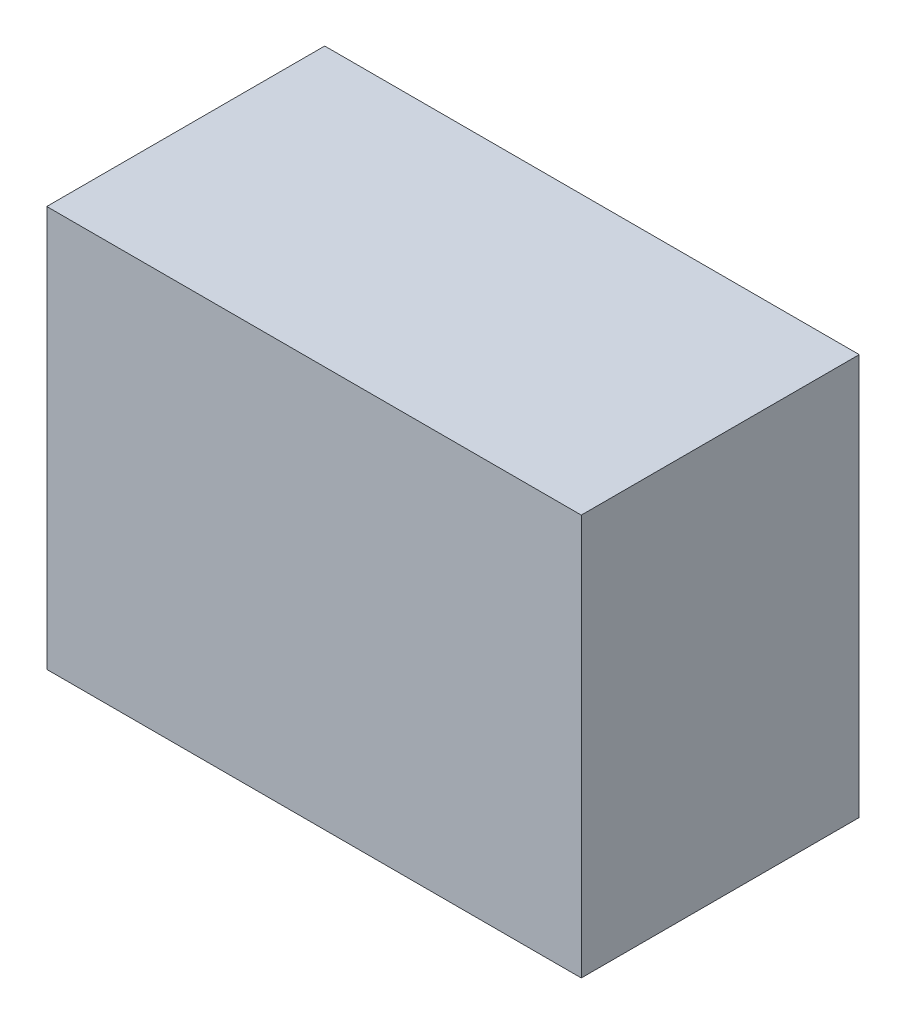
SolidWorks part; units mm, degrees
ref_plane "Front Plane" through (0, 0, 0) normal (0, 0, 1) x (1, 0, 0)
ref_plane "Top Plane" through (0, 0, 0) normal (0, 1, 0) x (1, 0, 0)
ref_plane "Right Plane" through (0, 0, 0) normal (1, 0, 0) x (0, 0, -1)
sketch "Sketch1" plane through (0, 0, 0) normal (0, 0, 1) x (1, 0, 0)
  line L0 (0, 0) -> (31.0378, 0) construction
  line L1 (0, 0) -> (0, 58.8262) construction
  line L3 (-10, 7.5) -> (10, 7.5)
  line L4 (-10, 7.5) -> (-10, -7.5)
  line L5 (-10, -7.5) -> (10, -7.5)
  line L6 (10, 7.5) -> (10, -7.5)
  line L7 (-10, 7.5) -> (10, -7.5) construction
  line L8 (-10, -7.5) -> (10, 7.5) construction
  dimension "D1" = 15
  dimension "D2" = 20
extrude "Boss-Extrude1" add sketch "Sketch1" along normal blind 10.4
